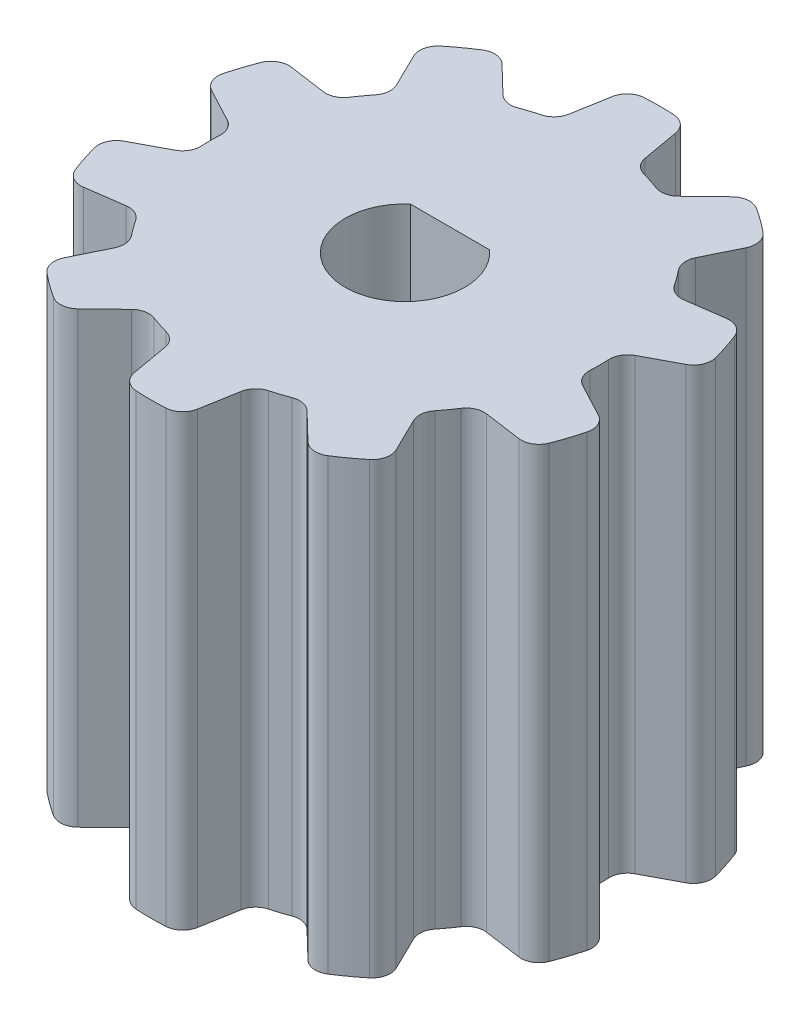
SolidWorks part; units mm, degrees
ref_plane "Front Plane" through (0, 0, 0) normal (0, 0, 1) x (1, 0, 0)
ref_plane "Top Plane" through (0, 0, 0) normal (0, 1, 0) x (1, 0, 0)
ref_plane "Right Plane" through (0, 0, 0) normal (1, 0, 0) x (0, 0, -1)
sketch "Sketch1" plane through (0, 0, 0) normal (0, 1, 0) x (1, 0, 0)
  circle A0 centre (0, 0) radius 2
  circle A1 centre (0, 0) radius 6.5
  dimension "D1" = 4
  dimension "D2" = 13
extrude "Boss-Extrude1" add sketch "Sketch1" along normal blind 15
sketch "Sketch2" plane through (0, 15, 0) normal (0, 1, 0) x (1, 0, 0)
  line L0 (0, 0) -> (0, 8.5) construction
  line L1 (0.9754, 8.4439) -> (1.3428, 6.3598)
  line L2 (0, 0) -> (-1.1591, 7.4018) construction
  line L3 (-0.9754, 8.4439) -> (-1.3428, 6.3598)
  line L4 (0, 0) -> (1.1591, 7.4018) construction
  circle A0 centre (0, 0) radius 7.5 construction
  circle A1 centre (0, 0) radius 8.5 construction
  circle A2 centre (0, 0) radius 6.5 construction
  arc A3 (1.3428, 6.3598) -> (-1.3428, 6.3598) centre (0, 0) ccw
  arc A4 (0.9754, 8.4439) -> (-0.9754, 8.4439) centre (0, 0) ccw
  point P12 (0, 10.5)
  dimension "D1" = 1
  dimension "D2" = 1
  dimension "D3" = 10
  dimension "D4" = 17.8
extrude "Boss-Extrude2" add sketch "Sketch2" against normal up to surface (15 mm away) up to face at (0, 0, 6.5)
fillet "Fillet1" radius 0.6 4 edges at (1.3428, 7.5, -6.3598) (0.9754, 7.5, -8.4439) (-0.9754, 7.5, -8.4439) (-1.3428, 7.5, -6.3598)
pattern_circular "CirPattern1" count 10 over 360 about axis through (0, 0, 0) along (0, 1, 0) of "Boss-Extrude2", "Fillet1"
sketch "Sketch3" plane through (0, 15, 0) normal (0, 1, 0) x (1, 0, 0)
  line L0 (-1.3229, 1.5) -> (1.3229, 1.5)
  line L1 (0, 1.5) -> (0, -2) construction
  circle A0 centre (0, 0) radius 2 construction
  arc A1 (1.3229, 1.5) -> (-1.3229, 1.5) centre (0, 0) ccw
  point P2 (0, -2)
  dimension "D1" = 3.5
extrude "Boss-Extrude3" add sketch "Sketch3" against normal up to surface (15 mm away) up to face at (0, 0, 0)
sketch "Sketch4" plane through (0, 0, 0) normal (0, -1, 0) x (1, 0, 0)
  line L0 (1.3229, -1.5) -> (-1.3229, -1.5) construction
  line L1 (1.3229, -1.5) -> (-1.3229, -1.5)
  arc A0 (1.3229, -1.5) -> (-1.3229, -1.5) centre (0, 0) ccw construction
  arc A1 (1.3229, -1.5) -> (-1.3229, -1.5) centre (0, 0) ccw
extrude "Boss-Extrude4" add sketch "Sketch4" against normal offset from surface (7 mm away) 8 up to face at (0, 15, 0)
